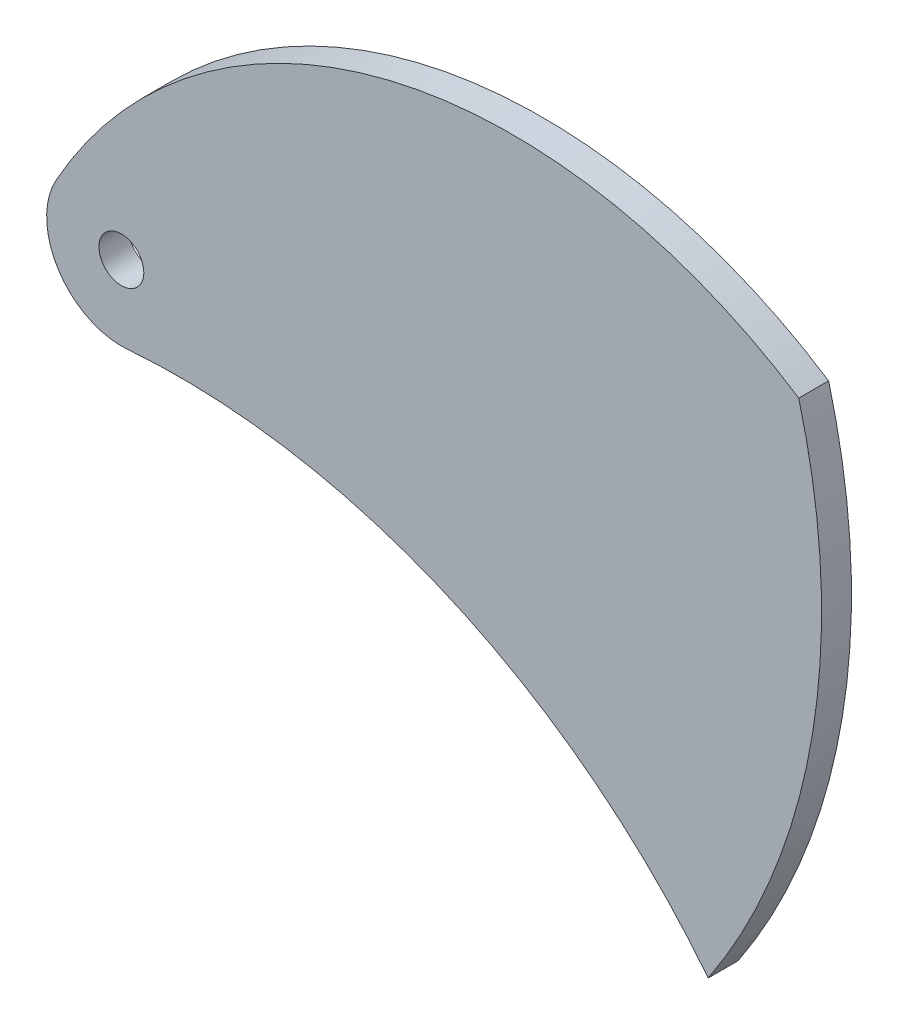
SolidWorks part; units mm, degrees
material "ABS"
ref_plane "前基準面" through (0, 0, 0) normal (0, 0, 1) x (1, 0, 0)
ref_plane "上基準面" through (0, 0, 0) normal (0, 1, 0) x (1, 0, 0)
ref_plane "右基準面" through (0, 0, 0) normal (1, 0, 0) x (0, 0, -1)
sketch "草圖1" plane through (0, 0, 0) normal (0, 0, 1) x (1, 0, 0)
  line L3 (0, 50) -> (0, 0) construction
  circle A80 centre (0, 0) radius 45 construction
  circle A81 centre (0, 0) radius 50 construction
  arc A84 (-43.6261, 24.4288) -> (-38.871, 17.0013) centre (-39.2635, 21.9859) ccw
  arc A85 (-38.871, 17.0013) -> (0, 0) centre (-35.3388, -27.8599) cw
  circle A87 centre (-39.2635, 21.9859) radius 1.5
  arc A91 (0, 0) -> (0, 50) centre (-37.4166, 25) ccw
  arc A118 (47.5528, 15.4508) -> (9.7519, 49.0398) centre (0, 0) ccw
  arc A119 (9.7519, 49.0398) -> (4.1574, 42.2222) centre (8.7767, 44.1358) ccw
  arc A120 (4.1574, 42.2222) -> (0, 0) centre (-37.4166, 25) cw
  arc A121 (0, 0) -> (47.5528, 15.4508) centre (12.2141, 43.3107) ccw
  circle A122 centre (8.7767, 44.1358) radius 1.5
  arc A123 (29.3893, -40.4508) -> (49.6531, 5.8795) centre (0, 0) ccw
  arc A124 (49.6531, 5.8795) -> (41.4404, 9.0935) centre (44.6878, 5.2915) ccw
  arc A125 (41.4404, 9.0935) -> (0, 0) centre (12.2141, 43.3107) cw
  arc A126 (0, 0) -> (29.3893, -40.4508) centre (44.9653, 1.7675) ccw
  circle A127 centre (44.6878, 5.2915) radius 1.5
  arc A128 (-29.3893, -40.4508) -> (20.9354, -45.4061) centre (0, 0) ccw
  arc A129 (20.9354, -45.4061) -> (21.4542, -36.6022) centre (18.8419, -40.8654) ccw
  arc A130 (21.4542, -36.6022) -> (0, 0) centre (44.9653, 1.7675) cw
  arc A131 (0, 0) -> (-29.3893, -40.4508) centre (15.576, -42.2183) ccw
  circle A132 centre (18.8419, -40.8654) radius 1.5
  arc A133 (-47.5528, 15.4508) -> (-36.7143, -33.942) centre (0, 0) ccw
  arc A134 (-36.7143, -33.942) -> (-28.181, -31.7148) centre (-33.0429, -30.5478) ccw
  arc A135 (-28.181, -31.7148) -> (0, 0) centre (15.576, -42.2183) cw
  arc A136 (0, 0) -> (-47.5528, 15.4508) centre (-35.3388, -27.8599) ccw
  circle A137 centre (-33.0429, -30.5478) radius 1.5
  arc A139 (-43.6261, 24.4288) -> (6.0546, 36.6299) centre (-13.0878, 7.3286) cw
  point P40 (0, 0)
  point P41 (6.5588, 34.5479)
  dimension "D1" = 100
  dimension "D2" = 90
  dimension "D3" = 3
  dimension "D5" = 35
  dimension "D4" = 5
extrude "填料-伸長1" add sketch "草圖1" along normal blind 2
